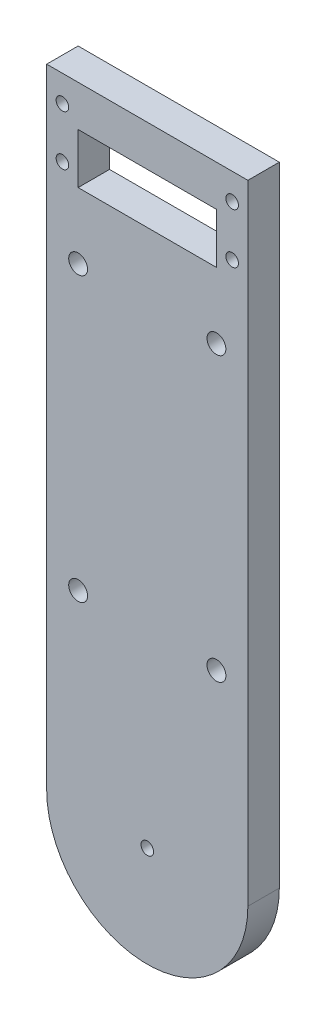
SolidWorks part; units mm, degrees
ref_plane "Front Plane" through (0, 0, 0) normal (0, 0, 1) x (1, 0, 0)
ref_plane "Top Plane" through (0, 0, 0) normal (0, 1, 0) x (1, 0, 0)
ref_plane "Right Plane" through (0, 0, 0) normal (1, 0, 0) x (0, 0, -1)
sketch "Sketch1" plane through (0, 0, 0) normal (0, 0, 1) x (1, 0, 0)
  line L1 (-16, 0) -> (-16, 80)
  line L2 (16, 0) -> (16, 80)
  line L3 (-16, 80) -> (16, 80)
  arc A0 (-16, 0) -> (16, 0) centre (0, 0) ccw
  circle A9 centre (0, 0) radius 1
  dimension "D1" = 32
  dimension "D2" = 2
  dimension "D6" = 80
extrude "Boss-Extrude1" add sketch "Sketch1" along normal blind 5
sketch "Sketch2" plane through (0, 0, 0) normal (0, 0, -1) x (-1, 0, 0)
  circle A0 centre (0, 0) radius 5.5
  dimension "D1" = 11
extrude "Cut-Extrude1" cut sketch "Sketch2" against normal blind 3
sketch "Sketch3" plane through (0, 0, 5) normal (0, 0, 1) x (1, 0, 0)
  line L0 (-16, 0) -> (-16, 80) construction
  line L1 (16, 0) -> (16, 80) construction
  line L2 (-16, 80) -> (16, 80) construction
  circle A0 centre (-11, 75) radius 1.5
  circle A1 centre (11, 75) radius 1.5
  circle A2 centre (-11, 30) radius 1.5
  circle A5 centre (11, 30) radius 1.5
  circle A8 centre (-11, -15) radius 1.5 [skipped]
  circle A9 centre (-11, -60) radius 1.5 [skipped]
  circle A10 centre (11, -60) radius 1.5 [skipped]
  circle A11 centre (11, -15) radius 1.5 [skipped]
  point P17 (0, 0)
  dimension "D1" = 3
  dimension "D2" = 3
  dimension "D5" = 5
  dimension "D3" = 5
  dimension "D4" = 5
  dimension "D6" = 5
  dimension "D8" = 45
  dimension "D10" = 45
  dimension "D7" = 4
  dimension "D9" = 4
extrude "Cut-Extrude2" cut sketch "Sketch3" against normal through all
sketch "Sketch4" plane through (0, 0, 5) normal (0, 0, 1) x (1, 0, 0)
  line L0 (16, 0) -> (16, 80) construction
  line L1 (-16, 80) -> (16, 80)
  line L2 (-16, 80) -> (-16, 100)
  line L3 (-16, 100) -> (16, 100)
  line L4 (16, 80) -> (16, 100)
  line L6 (-11, 93.5) -> (11, 93.5)
  line L7 (-11, 93.5) -> (-11, 85.5)
  line L8 (-11, 85.5) -> (11, 85.5)
  line L9 (11, 93.5) -> (11, 85.5)
  line L10 (-11, 93.5) -> (11, 85.5) construction
  line L11 (-11, 85.5) -> (11, 93.5) construction
  circle A0 centre (-13.5, 95.8) radius 1
  circle A1 centre (13.5, 95.8) radius 1
  circle A2 centre (-13.5, 87.8) radius 1
  circle A3 centre (13.5, 87.8) radius 1
  point P16 (0, 89.5)
  dimension "D2" = 2
  dimension "D1" = 20
  dimension "D3" = 2.5
  dimension "D4" = 2.5
  dimension "D5" = 8
  dimension "D6" = 7.8
  dimension "D7" = 5.5
  dimension "D8" = 8
  dimension "D9" = 22
  dimension "D10" = 5
extrude "Boss-Extrude2" add sketch "Sketch4" against normal blind 5
sketch "Sketch5" plane through (0, 0, 0) normal (0, 0, 1) x (1, 0, 0)
  line L1 (-8.1132, 75) -> (-9.5566, 77.5)
  line L2 (-9.5566, 77.5) -> (-12.4434, 77.5)
  line L3 (-12.4434, 77.5) -> (-13.8868, 75)
  line L4 (-13.8868, 75) -> (-12.4434, 72.5)
  line L5 (-12.4434, 72.5) -> (-9.5566, 72.5)
  line L6 (-9.5566, 72.5) -> (-8.1132, 75)
  line L7 (8.1132, 75) -> (9.5566, 72.5)
  line L8 (9.5566, 72.5) -> (12.4434, 72.5)
  line L9 (12.4434, 72.5) -> (13.8868, 75)
  line L10 (13.8868, 75) -> (12.4434, 77.5)
  line L11 (12.4434, 77.5) -> (9.5566, 77.5)
  line L12 (9.5566, 77.5) -> (8.1132, 75)
  line L13 (8.1132, 30) -> (9.5566, 27.5)
  line L14 (9.5566, 27.5) -> (12.4434, 27.5)
  line L15 (12.4434, 27.5) -> (13.8868, 30)
  line L16 (13.8868, 30) -> (12.4434, 32.5)
  line L17 (12.4434, 32.5) -> (9.5566, 32.5)
  line L18 (9.5566, 32.5) -> (8.1132, 30)
  line L19 (-8.1132, 30) -> (-9.5566, 32.5)
  line L20 (-9.5566, 32.5) -> (-12.4434, 32.5)
  line L21 (-12.4434, 32.5) -> (-13.8868, 30)
  line L22 (-13.8868, 30) -> (-12.4434, 27.5)
  line L23 (-12.4434, 27.5) -> (-9.5566, 27.5)
  line L24 (-9.5566, 27.5) -> (-8.1132, 30)
  circle A0 centre (-11, 75) radius 2.5 construction
  circle A1 centre (11, 75) radius 2.5 construction
  circle A2 centre (11, 30) radius 2.5 construction
  circle A3 centre (-11, 30) radius 2.5 construction
  dimension "D1" = 5
extrude "Cut-Extrude3" cut sketch "Sketch5" along normal blind 1.5
